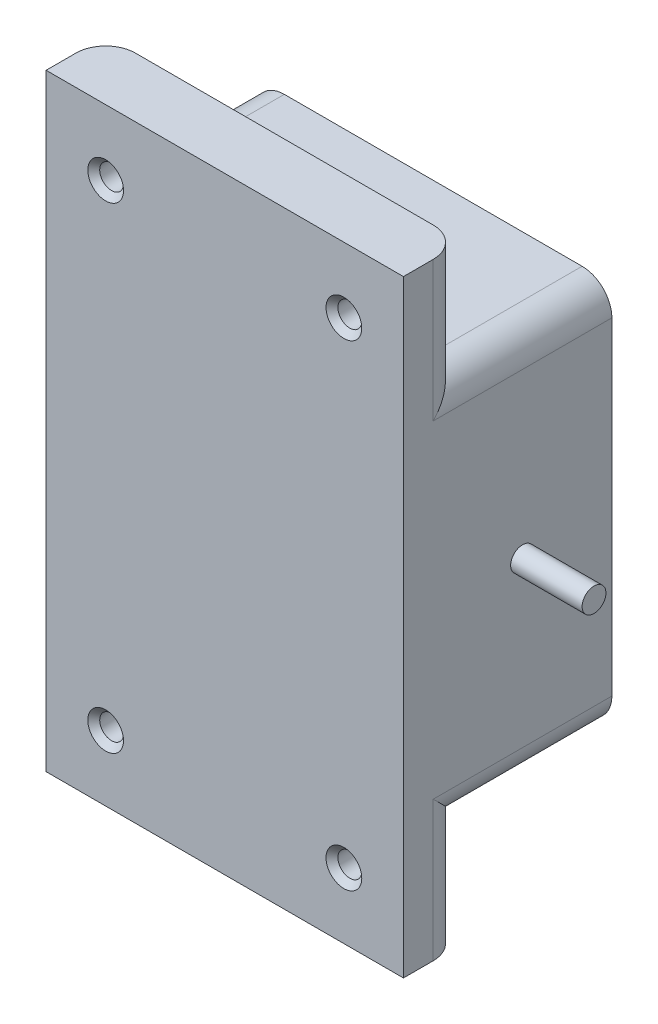
SolidWorks part; units mm, degrees
ref_plane "Front Plane" through (0, 0, 0) normal (0, 0, 1) x (1, 0, 0)
ref_plane "Top Plane" through (0, 0, 0) normal (0, 1, 0) x (1, 0, 0)
ref_plane "Right Plane" through (0, 0, 0) normal (1, 0, 0) x (0, 0, -1)
sketch "Sketch3" plane through (0, 0, 0) normal (0, 0, 1) x (1, 0, 0)
  line L0 (0, 0) -> (0, 40) construction
  line L5 (-30, 51) -> (30, 51)
  line L6 (-30, 51) -> (-30, -51)
  line L7 (-30, -51) -> (30, -51)
  line L8 (30, 51) -> (30, -51)
  line L9 (-20, 40) -> (20, 40) construction
  line L16 (-30, 0) -> (30, 0) construction
  circle A10 centre (-20, 40) radius 2
  circle A11 centre (20, 40) radius 2
  circle A12 centre (20, -40) radius 2
  circle A13 centre (-20, -40) radius 2
  point P0 (0, 0)
  point P10 (0, 40)
  dimension "D1" = 102
  dimension "D2" = 60
extrude "Boss-Extrude1" add sketch "Sketch3" along normal blind 10
sketch "Sketch4" plane through (0, 0, 0) normal (0, 0, -1) x (-1, 0, 0)
  line L0 (30, 51) -> (30, -51) construction
  line L1 (-30, 32.5) -> (30, 32.5)
  line L2 (-30, 32.5) -> (-30, -32.5)
  line L3 (-30, -32.5) -> (30, -32.5)
  line L4 (30, 32.5) -> (30, -32.5)
  line L5 (-30, 32.5) -> (30, -32.5) construction
  line L6 (-30, -32.5) -> (30, 32.5) construction
  point P0 (0, 0)
  dimension "D1" = 65
extrude "Boss-Extrude2" add sketch "Sketch4" along normal blind 25 contours L2 L1 L4 L3
fillet "Fillet1" radius 5 8 edges at (30, 41.75, 0) (30, -41.75, 0) (-30, -41.75, 0) (-30, 41.75, 0) (-30, 32.5, -12.5) (-30, -32.5, -12.5) (30, -32.5, -12.5) (30, 32.5, -12.5)
sketch "Sketch6" plane through (0, 0, -25) normal (0, 0, -1) x (-1, 0, 0)
  line L0 (0, 0) -> (0, -5) construction
  line L1 (-30, -5) -> (30, -5) construction
  line L2 (-30, 27.5) -> (-30, -27.5) construction
  line L3 (30, 27.5) -> (30, -27.5) construction
  text T0 "<b>MLA-30+</b>" font "Century Gothic" height 10
extrude "Cut-Extrude1" cut sketch "Sketch6" against normal blind 2
sketch "Sketch7" plane through (30, 0, 0) normal (1, 0, 0) x (0, 0, -1)
  line L0 (-10, 0) -> (25, -0.0982) construction
  line L1 (-10, -51) -> (-10, 51) construction
  line L2 (10, 27.5) -> (10, -27.5) construction
  line L3 (25, 27.5) -> (-5, 27.5) construction
  line L4 (-5, -27.5) -> (25, -27.5) construction
  circle A0 centre (10, 0) radius 2
extrude "Boss-Extrude3" add sketch "Sketch7" along normal blind 12
sketch "Sketch8" plane through (-30, 0, 0) normal (-1, 0, 0) x (0, 0, 1)
  line L0 (-25, 0) -> (10, 0) construction
  line L1 (-25, 27.5) -> (-25, -27.5) construction
  line L2 (10, 51) -> (10, -51) construction
  line L3 (-10, 27.5) -> (-10, -27.5) construction
  line L4 (5, 27.5) -> (-25, 27.5) construction
  line L5 (-25, -27.5) -> (5, -27.5) construction
  circle A0 centre (-10, 0) radius 2
extrude "Boss-Extrude4" add sketch "Sketch8" along normal blind 12
chamfer "Chamfer2" distance 1 angle 45 4 edges at (22, 40, 10) (-18, 40, 10) (18, -40, 10) (-22, -40, 10)
